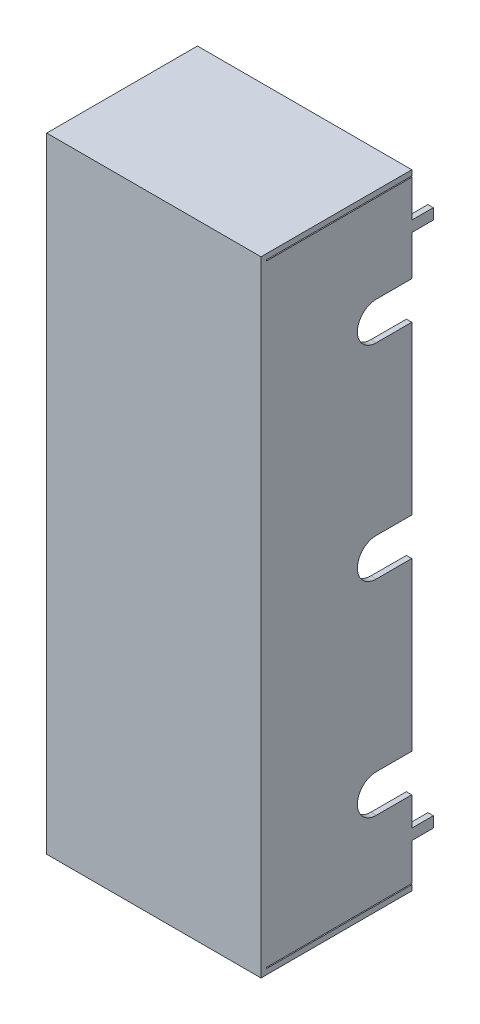
SolidWorks part; units mm, degrees
material "Aluminium"
ref_plane "Plan de face" through (0, 0, 0) normal (0, 0, 1) x (1, 0, 0)
ref_plane "Plan de dessus" through (0, 0, 0) normal (0, 1, 0) x (1, 0, 0)
ref_plane "Plan de droite" through (0, 0, 0) normal (1, 0, 0) x (0, 0, -1)
sketch "Esquisse1" plane through (0, 0, 0) normal (0, 0, 1) x (1, 0, 0)
  line L0 (91.7423, 30.4868) -> (91.7423, -26.3132)
  line L3 (92.2423, 30.4868) -> (92.2423, -26.3132)
  line L5 (93.2423, -10.4289) -> (93.2423, -24.4289) construction
  line L7 (110.1423, 27.5711) -> (93.2423, 27.5711) construction
  line L8 (101.6923, 27.5711) -> (101.6923, 23.1567) construction
  line L9 (111.1423, 30.4868) -> (111.1423, -26.3132)
  line L11 (92.2423, 30.4868) -> (91.7423, 30.4868)
  line L12 (111.6423, 30.4868) -> (111.6423, -26.3132)
  line L13 (91.7423, 31.0868) -> (91.7423, 30.5868)
  line L14 (91.7423, 31.0868) -> (111.6423, 31.0868)
  line L15 (91.7423, 30.5868) -> (111.6423, 30.5868)
  line L16 (111.6423, 31.0868) -> (111.6423, 30.5868)
  line L17 (91.7423, 2.0868) -> (98.281, 2.0868) construction
  line L18 (111.6423, -26.4132) -> (111.6423, -26.9132)
  line L19 (91.7423, -26.4132) -> (111.6423, -26.4132)
  line L20 (91.7423, -26.9132) -> (111.6423, -26.9132)
  line L22 (111.6423, 30.4868) -> (111.1423, 30.4868)
  line L23 (111.6423, -26.3132) -> (111.1423, -26.3132)
  line L24 (92.2423, -26.3132) -> (91.7423, -26.3132)
  line L26 (91.7423, -26.4132) -> (91.7423, -26.9132)
  dimension "D1" = 0.5
  dimension "D2" = 1
  dimension "D4" = 0.1
  dimension "D5" = 0.5
  dimension "D8" = 0.1
extrude "Extrusion1" add sketch "Esquisse1" along normal blind 13.5
sketch "Esquisse2" plane through (0, 0, 13.5) normal (0, 0, 1) x (1, 0, 0)
  line L0 (91.7423, 31.0868) -> (91.7423, -26.9132)
  line L1 (91.7423, 31.0868) -> (111.6423, 31.0868)
  line L2 (91.7423, -26.9132) -> (111.6423, -26.9132)
  line L3 (111.6423, 31.0868) -> (111.6423, -26.9132)
  line L5 (91.7423, 30.4868) -> (91.7423, -26.3132) construction
  line L6 (111.6423, -26.3132) -> (111.6423, 30.4868) construction
extrude "Extrusion2" add sketch "Esquisse2" along normal blind 0.5
sketch "Esquisse3" plane through (111.6423, 0, 0) normal (1, 0, 0) x (0, 0, -1)
  line L0 (-1.95, 20.5711) -> (-8.8811, 20.5711) construction
  line L1 (0, 22.3211) -> (0, 18.8211)
  line L2 (0, 22.3211) -> (-3.3, 22.3211)
  line L3 (0, 18.8211) -> (-3.3, 18.8211)
  line L4 (0, 3.3211) -> (0, -0.1789)
  line L5 (0, -26.3132) -> (0, 30.4868) construction
  line L6 (0, 3.3211) -> (-3.3, 3.3211)
  line L7 (0, -0.1789) -> (-3.3, -0.1789)
  line L8 (-1.95, 1.5711) -> (-8.8811, 1.5711) construction
  line L9 (0, -15.6789) -> (0, -19.1789)
  line L10 (0, -15.6789) -> (-3.3, -15.6789)
  line L11 (0, -19.1789) -> (-3.3, -19.1789)
  line L12 (-1.95, -17.4289) -> (-8.8811, -17.4289) construction
  line L13 (0, -26.3132) -> (0, 30.4868) construction
  circle A0 centre (-3.3, 20.5711) radius 1.35 construction
  arc A1 (-3.3, 22.3211) -> (-3.3, 18.8211) centre (-3.3, 20.5711) ccw
  arc A2 (-3.3, 3.3211) -> (-3.3, -0.1789) centre (-3.3, 1.5711) ccw
  arc A3 (-3.3, -15.6789) -> (-3.3, -19.1789) centre (-3.3, -17.4289) ccw
  dimension "D2" = 3.3
  dimension "D1" = 3.5
extrude "Enlèv. mat.-Extru.1" cut sketch "Esquisse3" against normal blind 10.5
sketch "Esquisse4" plane through (0, 0, 0) normal (0, 0, -1) x (-1, 0, 0)
  line L0 (-111.6423, 27.0368) -> (-111.6423, 26.0368)
  line L1 (-111.6423, 27.0368) -> (-111.1423, 27.0368)
  line L2 (-111.6423, 26.0368) -> (-111.1423, 26.0368)
  line L3 (-111.1423, 27.0368) -> (-111.1423, 26.0368)
  line L4 (-111.6423, 31.0868) -> (-91.7423, 31.0868) construction
  line L5 (-91.7423, -26.9132) -> (-111.6423, -26.9132) construction
  line L6 (-92.2423, 27.0368) -> (-92.2423, 26.0368)
  line L7 (-92.2423, 27.0368) -> (-91.7423, 27.0368)
  line L8 (-92.2423, 26.0368) -> (-91.7423, 26.0368)
  line L9 (-91.7423, 27.0368) -> (-91.7423, 26.0368)
  line L12 (-91.7423, 2.0868) -> (-105.9959, 2.0868) construction
  line L14 (-111.6423, -22.8632) -> (-111.1423, -22.8632)
  line L15 (-111.6423, -22.8632) -> (-111.6423, -21.8632)
  line L16 (-111.1423, -22.8632) -> (-111.1423, -21.8632)
  line L17 (-111.6423, -21.8632) -> (-111.1423, -21.8632)
  line L20 (-92.2423, -22.8632) -> (-91.7423, -22.8632)
  line L21 (-92.2423, -22.8632) -> (-92.2423, -21.8632)
  line L22 (-91.7423, -22.8632) -> (-91.7423, -21.8632)
  line L23 (-92.2423, -21.8632) -> (-91.7423, -21.8632)
  dimension "D1" = 49.9
  dimension "D2" = 1
  dimension "D3" = 1
extrude "Extrusion3" add sketch "Esquisse4" along normal blind 2
